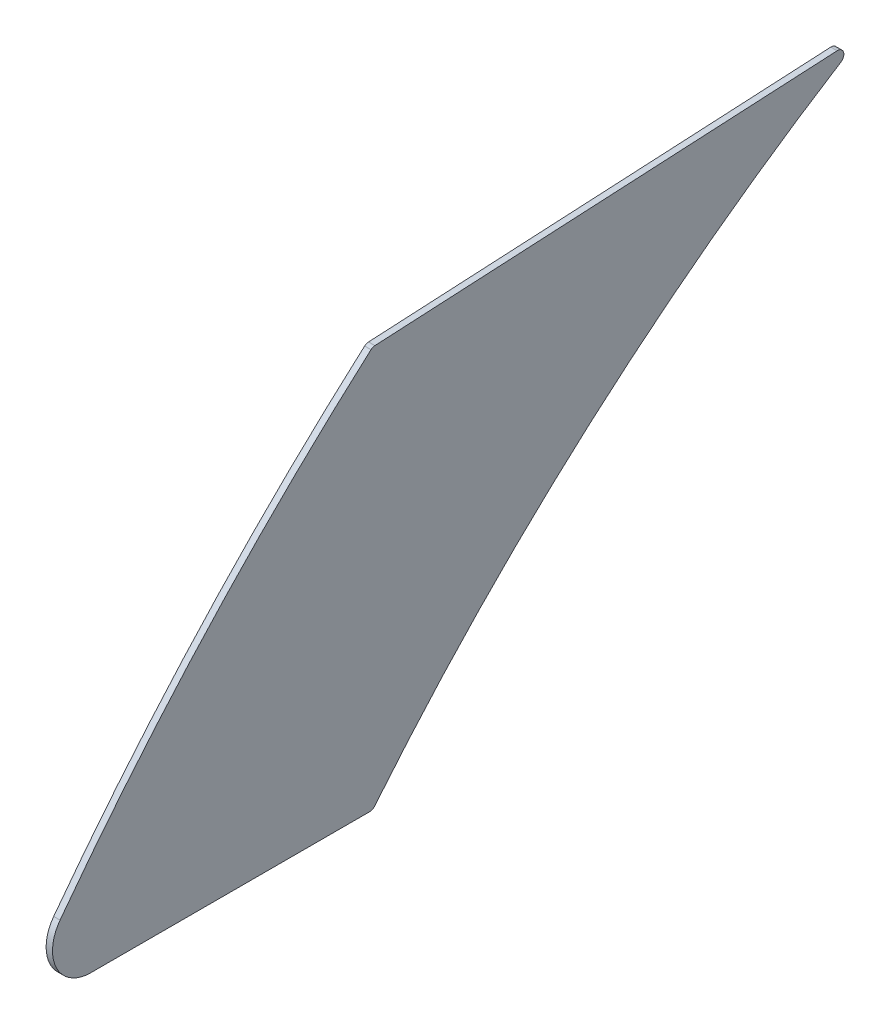
SolidWorks part; units mm, degrees
ref_plane "Front Plane" through (0, 0, 0) normal (0, 0, 1) x (1, 0, 0)
ref_plane "Top Plane" through (0, 0, 0) normal (0, 1, 0) x (1, 0, 0)
ref_plane "Right Plane" through (0, 0, 0) normal (1, 0, 0) x (0, 0, -1)
sketch "Sketch1" plane through (0, 0, 0) normal (1, 0, 0) x (0, 0, -1)
  line L0 (0.3485, 0.0183) -> (72.9858, 3.825)
  line L1 (-44.3055, -63) -> (-0.4751, -63)
  arc A0 (0.2996, -62.6323) -> (73.5686, 1.9787) centre (232.7073, -252.3339) cw
  arc A1 (-49.1194, -53.4186) -> (-0.2619, -0.2315) centre (231.6898, -262.3354) cw
  arc A2 (-44.3055, -63) -> (-49.1194, -53.4186) centre (-44.3055, -57) cw
  arc A3 (-0.4751, -63) -> (0.2996, -62.6323) centre (-0.4751, -62) ccw
  arc A4 (0.3485, 0.0183) -> (-0.2619, -0.2315) centre (0.4009, -0.9804) ccw
  arc A5 (72.9858, 3.825) -> (73.5686, 1.9787) centre (73.0381, 2.8264) cw
  point P9 (-56, -63)
  point P15 (0, -63)
  point P18 (0, 0)
  point P21 (76.8945, 4.0299)
  dimension "D5" = 350
  dimension "D6" = 300
  dimension "D7" = 6
  dimension "D4" = 1
  dimension "D1" = 77
  dimension "D2" = 63
  dimension "D3" = 56
  dimension "D8" = 3
extrude "Boss-Extrude1" add sketch "Sketch1" along normal blind 1
